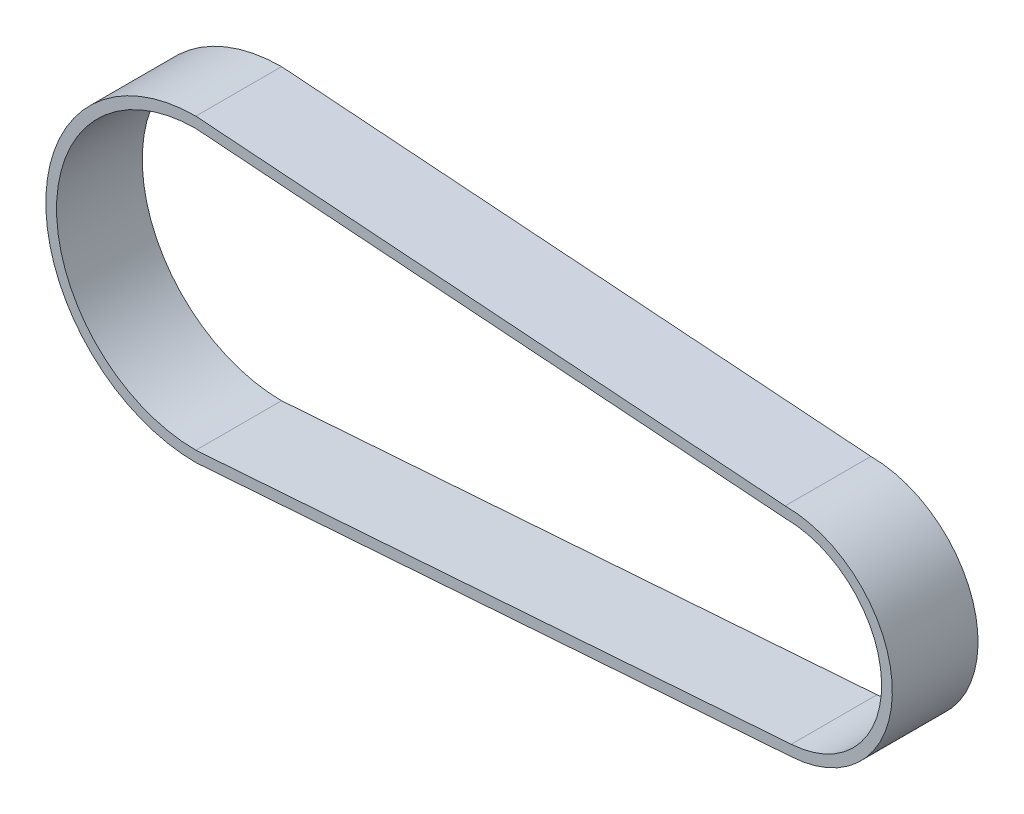
SolidWorks part; units mm, degrees
ref_plane "Plan de face" through (0, 0, 0) normal (0, 0, 1) x (1, 0, 0)
ref_plane "Plan de dessus" through (0, 0, 0) normal (0, 1, 0) x (1, 0, 0)
ref_plane "Plan de droite" through (0, 0, 0) normal (1, 0, 0) x (0, 0, -1)
sketch "Esquisse1" plane through (0, 0, 0) normal (0, 0, 1) x (1, 0, 0)
  line L0 (0, 0) -> (25, 0) construction
  line L1 (0, 0) -> (-30, 0) construction
  line L2 (-30, 13) -> (25, 9)
  line L3 (-30, -13) -> (25.5671, -8.9821)
  line L4 (-30, -14) -> (25.5671, -9.9839)
  line L5 (25, 10) -> (-30, 14)
  circle A0 centre (-30, 0) radius 13 construction
  circle A1 centre (25, 0) radius 9 construction
  circle A2 centre (25, 0) radius 10 construction
  circle A3 centre (-30, 0) radius 14 construction
  arc A4 (-30, 14) -> (-30, -14) centre (-30, 0) ccw
  arc A5 (-30, 13) -> (-30, -13) centre (-30, 0) ccw
  arc A6 (25, 10) -> (25.5671, -9.9839) centre (25, 0) cw
  arc A7 (25.5671, -8.9821) -> (25, 9) centre (25, 0) ccw
extrude "Boss.-Extru.1" add sketch "Esquisse1" along normal blind 8
